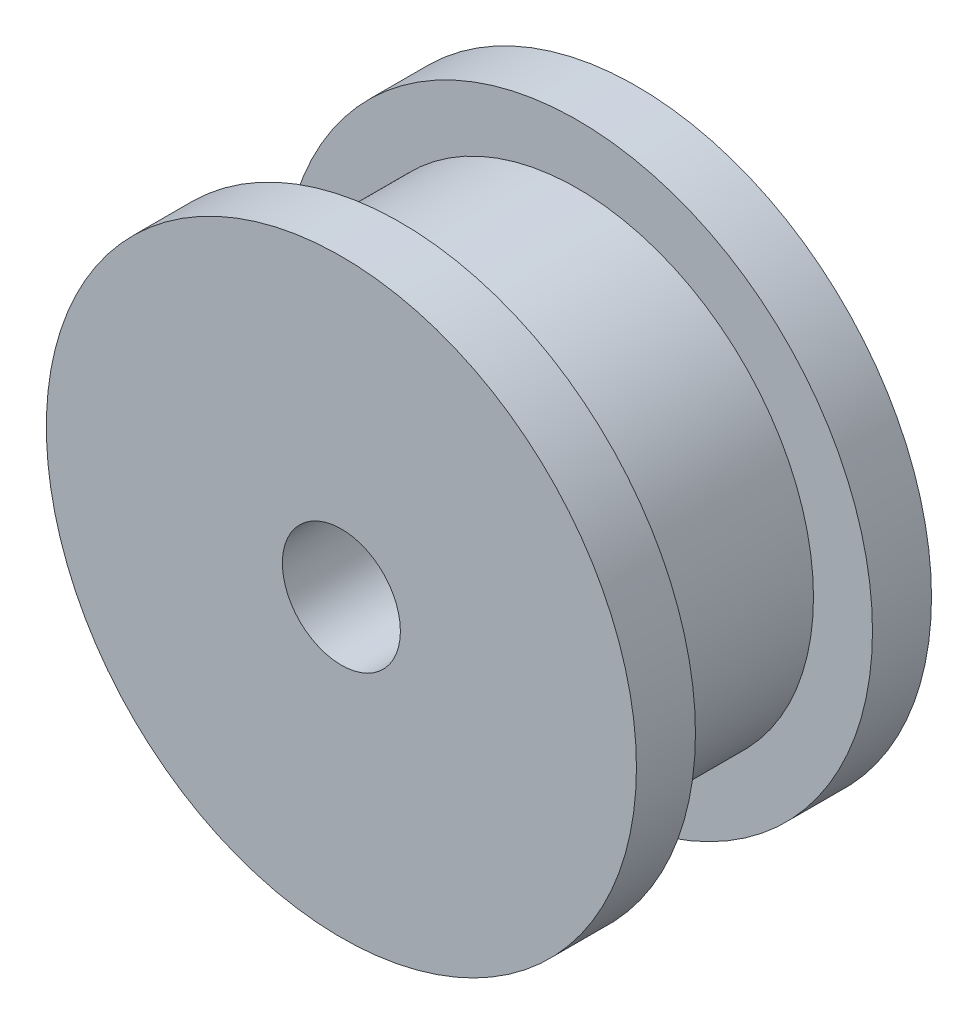
SolidWorks part; units mm, degrees
ref_plane "前视基准面" through (0, 0, 0) normal (0, 0, 1) x (1, 0, 0)
ref_plane "上视基准面" through (0, 0, 0) normal (0, 1, 0) x (1, 0, 0)
ref_plane "右视基准面" through (0, 0, 0) normal (1, 0, 0) x (0, 0, -1)
sketch "草图1" plane through (0, 0, 0) normal (0, 0, 1) x (1, 0, 0)
  circle A0 centre (0, 0) radius 50
extrude "凸台-拉伸1" add sketch "草图1" along normal blind 50
ref_plane "基准面1" through (0, 0, 25) normal (0, 0, 1) x (1, 0, 0)
sketch "草图2" plane through (0, 0, 25) normal (0, 0, 1) x (1, 0, 0)
  circle A0 centre (0, 0) radius 40
extrude "切除-拉伸1" cut sketch "草图2" against normal blind 15 and the other way blind 15 from offset 0 flip side to cut
sketch "草图3" plane through (0, 0, 25) normal (0, 0, 1) x (1, 0, 0)
  circle A0 centre (0, 0) radius 10
extrude "切除-拉伸2" cut sketch "草图3" against normal through all both and the other way through all from offset 0
